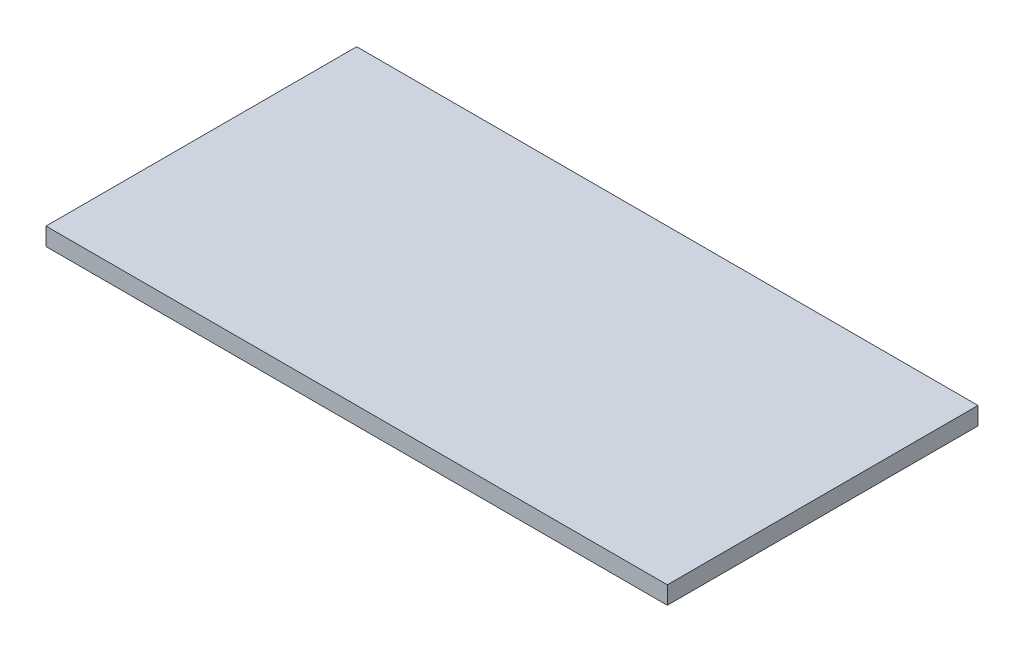
SolidWorks part; units mm, degrees
ref_plane "Front Plane" through (0, 0, 0) normal (0, 0, 1) x (1, 0, 0)
ref_plane "Top Plane" through (0, 0, 0) normal (0, 1, 0) x (1, 0, 0)
ref_plane "Right Plane" through (0, 0, 0) normal (1, 0, 0) x (0, 0, -1)
sketch "Sketch1" plane through (0, 0, 0) normal (0, 1, 0) x (1, 0, 0)
  line L1 (0, 0) -> (88.9, 0)
  line L2 (0, 0) -> (0, 44.45)
  line L3 (0, 44.45) -> (88.9, 44.45)
  line L4 (88.9, 0) -> (88.9, 44.45)
  dimension "D1" = 88.9
  dimension "D2" = 44.45
extrude "Boss-Extrude1" add sketch "Sketch1" along normal blind 2.54
